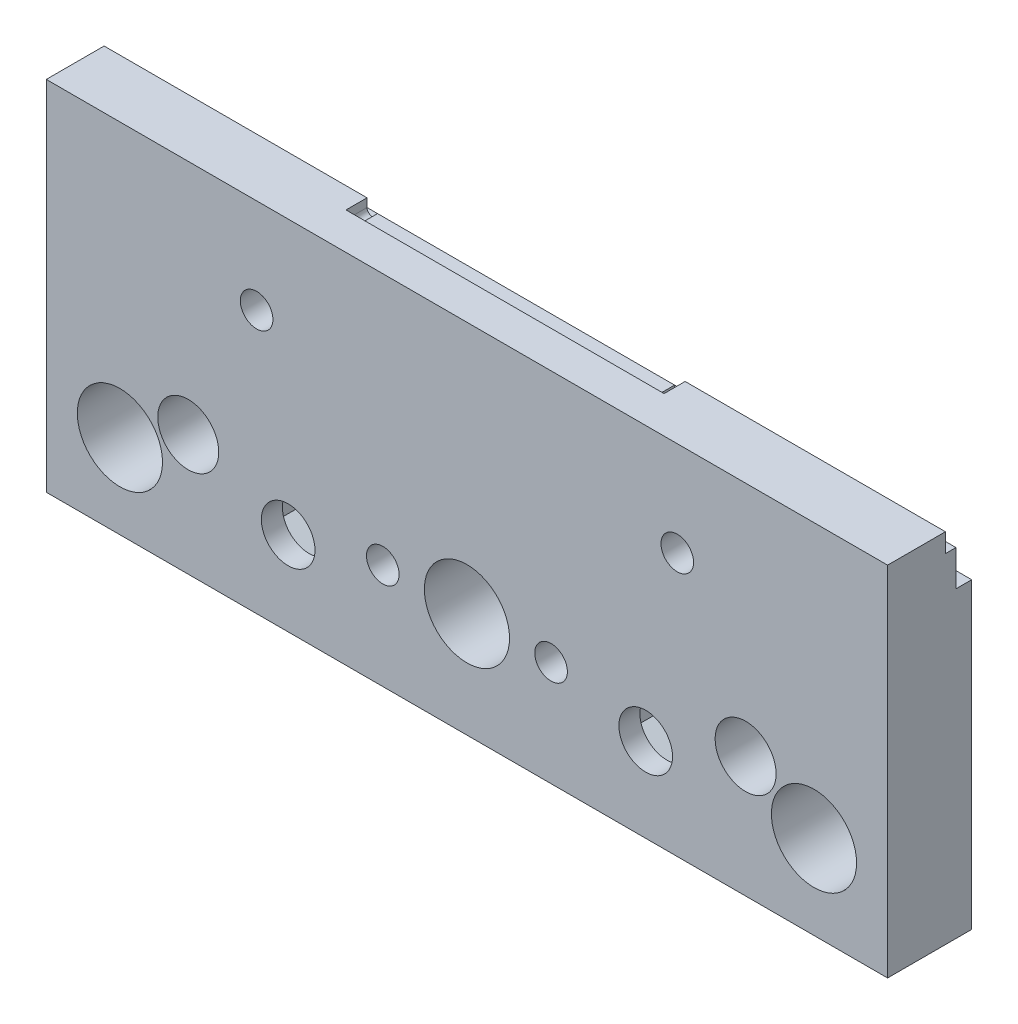
SolidWorks part; units mm, degrees
ref_plane "前视基准面" through (0, 0, 0) normal (0, 0, 1) x (1, 0, 0)
ref_plane "上视基准面" through (0, 0, 0) normal (0, 1, 0) x (1, 0, 0)
ref_plane "右视基准面" through (0, 0, 0) normal (1, 0, 0) x (0, 0, -1)
sketch "前视图草图" plane through (0, 0, 0) normal (0, 0, 1) x (1, 0, 0)
  line L0 (0, 0) -> (44.4821, 0) construction
  line L1 (0, 0) -> (0, 28.3185) construction
sketch "草图2" plane through (0, 0, 0) normal (0, 0, 1) x (1, 0, 0)
  line L0 (0, 0) -> (80, 0)
  line L1 (-200000, 0) -> (200044.4821, 0) construction
  line L2 (80, 0) -> (80, 34)
  line L3 (80, 34) -> (0, 34)
  line L4 (0, -200000) -> (0, 200028.3185) construction
  line L5 (0, 34) -> (0, 0)
  circle A0 centre (7, 8) radius 4.05
  circle A1 centre (40, 10) radius 4.05
  circle A2 centre (73, 8) radius 4.05
  dimension "D3" = 8
  dimension "D5" = 10
  dimension "D9" = 8.1
  dimension "D10" = 8.1
  dimension "D11" = 8.1
  dimension "D1" = 34
  dimension "D2" = 80
  dimension "D4" = 7
  dimension "D6" = 7
  dimension "D7" = 8
  dimension "D8" = 40
extrude "凸台-拉伸1" add sketch "草图2" along normal blind 8
sketch "草图3" plane through (0, 0, 8) normal (0, 0, 1) x (1, 0, 0)
  line L0 (16.088, 8) -> (31.4805, 8) construction
  line L1 (7, 8) -> (7, 16.8386) construction
  line L2 (73, 8) -> (73, 16.5917) construction
  line L4 (-200000, 0) -> (200044.4821, 0) construction
  circle A2 centre (23, 8) radius 2.55
  circle A3 centre (57, 8) radius 2.55
  dimension "D4" = 5.1
  dimension "D5" = 5.1
  dimension "D1" = 8
  dimension "D2" = 16
  dimension "D3" = 16
extrude "切除-拉伸1" cut sketch "草图3" against normal through all
sketch "草图4" plane through (80, 0, 0) normal (1, 0, 0) x (0, 0, -1)
  line L1 (0, -200000) -> (0, 200028.3185) construction
  line L2 (-1.5, 32.2) -> (-2.5, 32.2)
  line L3 (-2.5, 32.2) -> (-2.5, 34)
  line L4 (-8, 34) -> (0, 34) construction
  line L5 (-2.5, 34) -> (0, 34)
  line L6 (-1.5, 32.2) -> (-1.5, 28.8)
  line L7 (-1.5, 28.8) -> (0, 28.8)
  line L8 (0, 28.8) -> (0, 34)
  dimension "D1" = 3.4
  dimension "D2" = 2.5
  dimension "D3" = 1.5
  dimension "D4" = 1.8
extrude "切除-拉伸2" cut sketch "草图4" against normal through all
sketch "草图5" plane through (0, 0, 8) normal (0, 0, 1) x (1, 0, 0)
  line L0 (40, 10) -> (56.5376, 10) construction
  circle A0 centre (40, 10) radius 8 construction
  circle A1 centre (48, 10) radius 1.55
  circle A2 centre (32, 10) radius 1.55
  dimension "D1" = 3.1
  dimension "D2" = 3.1
  dimension "D3" = 16
extrude "切除-拉伸3" cut sketch "草图5" against normal through all
sketch "草图7" plane through (0, 0, 0) normal (0, 0, -1) x (-1, 0, 0)
  line L0 (-40, 12) -> (-40, -8.3696) construction
  line L1 (-23, 10) -> (-23, -2.3368) construction
  line L2 (200000, 0) -> (-200044.4821, 0) construction
  line L6 (-27.05, 10) -> (-27.05, 2.5)
  line L7 (-29.55, 0) -> (-16.45, 0)
  line L8 (-18.95, 2.5) -> (-18.95, 10)
  line L9 (-23, 8) -> (-23, 15.9045) construction
  line L13 (0, -200000) -> (0, 200028.3185) construction
  line L14 (-57, 8) -> (-57, 15.9045) construction
  line L15 (-57, 10) -> (-57, -2.3368) construction
  line L16 (-61.05, 2.5) -> (-61.05, 10)
  line L17 (-50.45, 0) -> (-63.55, 0)
  line L18 (-52.95, 10) -> (-52.95, 2.5)
  arc A1 (-18.95, 10) -> (-27.05, 10) centre (-23, 10) ccw
  arc A4 (-29.55, 0) -> (-27.05, 2.5) centre (-29.55, 2.5) ccw
  arc A5 (-18.95, 2.5) -> (-16.45, 0) centre (-16.45, 2.5) ccw
  arc A7 (-61.05, 2.5) -> (-63.55, 0) centre (-63.55, 2.5) cw
  arc A8 (-50.45, 0) -> (-52.95, 2.5) centre (-50.45, 2.5) cw
  arc A9 (-61.05, 10) -> (-52.95, 10) centre (-57, 10) cw
  dimension "D1" = 40
  dimension "D4" = 8.1
  dimension "D7" = 2.5
  dimension "D8" = 2.5
  dimension "D3" = 10
extrude "切除-拉伸4" [suppressed] cut sketch "草图7" against normal blind 6
sketch "草图8" plane through (0, 0, 0) normal (0, 0, -1) x (-1, 0, 0)
  line L0 (-40, 10) -> (-57.3165, 10) construction
  line L1 (-40, 20) -> (-40, 35.6562) construction
  line L2 (-30.5, 12.85) -> (-49.5, 12.85)
  line L3 (-49.5, 7.15) -> (-30.5, 7.15)
  line L4 (200000, 0) -> (-200044.4821, 0) construction
  line L5 (-80, 0) -> (-80, 28.8) construction
  line L6 (-48, 6.7091) -> (-45.15, 8.3546)
  line L7 (-45.15, 8.3546) -> (-45.15, 11.6454)
  line L8 (-45.15, 11.6454) -> (-48, 13.2909)
  line L9 (-48, 13.2909) -> (-50.85, 11.6454)
  line L10 (-50.85, 11.6454) -> (-50.85, 8.3546)
  line L11 (-50.85, 8.3546) -> (-48, 6.7091)
  line L12 (-34.85, 11.6454) -> (-34.85, 8.3546)
  line L13 (-34.85, 8.3546) -> (-32, 6.7091)
  line L14 (-32, 6.7091) -> (-29.15, 8.3546)
  line L15 (-29.15, 8.3546) -> (-29.15, 11.6454)
  line L16 (-29.15, 11.6454) -> (-32, 13.2909)
  line L17 (-32, 13.2909) -> (-34.85, 11.6454)
  arc A0 (-30.5, 7.15) -> (-30.5, 12.85) centre (-30.5, 10) ccw
  arc A1 (-49.5, 12.85) -> (-49.5, 7.15) centre (-49.5, 10) ccw
  circle A2 centre (-48, 10) radius 2.85 construction
  circle A3 centre (-32, 10) radius 2.85 construction
  dimension "D1" = 5.7
  dimension "D2" = 9.5
  dimension "D3" = 9.5
  dimension "D4" = 10
  dimension "D5" = 5.7
sketch "草图11" plane through (0, 0, 0) normal (0, 0, -1) x (-1, 0, 0)
  line L0 (0, 34) -> (-80, 34) construction
  line L1 (-80, 0) -> (-80, 28.8) construction
  line L2 (0, -200000) -> (0, 200028.3185) construction
  line L3 (-40, 20) -> (-40, 13.5744) construction
  line L4 (-28.772, 25) -> (-45.9396, 25) construction
  circle A0 centre (-60, 25) radius 1.55
  circle A1 centre (-20, 25) radius 1.55
  point P23 (-40, 20)
  dimension "D1" = 3.1
  dimension "D2" = 3.1
  dimension "D3" = 20
  dimension "D4" = 20
  dimension "D5" = 9
sketch "草图20" plane through (0, 0, 0) normal (0, 0, -1) x (-1, 0, 0)
  circle A0 centre (-40, 10) radius 5.5
  dimension "D1" = 11
extrude "切除-拉伸15" cut sketch "草图8" against normal blind 4.5 contours L10 L11 L6 L7 L8 L9 | L13 L14 L15 L16 L17 L12
extrude "切除-拉伸7" cut sketch "草图11" against normal through all contours A0 | A1
sketch "草图12" plane through (0, 0, 0) normal (0, 0, -1) x (-1, 0, 0)
  line L0 (-62.5, 22.15) -> (-57.5, 22.15)
  line L1 (-57.5, 27.85) -> (-62.5, 27.85)
  line L4 (-80, 0) -> (-80, 28.8) construction
  line L5 (-39.1423, 25) -> (-43.2672, 25) construction
  line L6 (-60, 21) -> (-60, 25.2385) construction
  line L7 (-20, 21) -> (-20, 26.1603) construction
  line L8 (-40, 20) -> (-40, 24.3689) construction
  line L9 (-17.5, 27.85) -> (-22.5, 27.85)
  line L10 (-22.5, 22.15) -> (-17.5, 22.15)
  line L11 (0, -200000) -> (0, 200028.3185) construction
  line L12 (0, 34) -> (-80, 34) construction
  arc A0 (-62.5, 27.85) -> (-62.5, 22.15) centre (-62.5, 25) ccw
  arc A1 (-57.5, 22.15) -> (-57.5, 27.85) centre (-57.5, 25) ccw
  arc A4 (-17.5, 22.15) -> (-17.5, 27.85) centre (-17.5, 25) ccw
  arc A5 (-22.5, 27.85) -> (-22.5, 22.15) centre (-22.5, 25) ccw
  point P16 (-38, 21)
  point P28 (-40, 25)
  dimension "D2" = 20
  dimension "D3" = 5
  dimension "D4" = 2.5
  dimension "D5" = 20
  dimension "D6" = 9
  dimension "D1" = 2
sketch "草图19" plane through (0, 0, 2.5) normal (0, 0, -1) x (-1, 0, 0)
  line L0 (0, 34) -> (-80, 34) construction
  line L1 (-25, 34) -> (-55.2479, 34)
  line L2 (-25, 34) -> (-25, 33.2)
  line L3 (-26, 33.2) -> (-54.2479, 33.2)
  line L4 (-55.2479, 34) -> (-55.2479, 33.2)
  line L5 (0, -200000) -> (0, 200028.3185) construction
  line L7 (0, 32.2) -> (-80, 32.2) construction
  line L8 (-56.3335, 32.7) -> (-52.9089, 32.7) construction
  line L9 (-55.2479, 1028.5823) -> (-55.2479, 33.2) construction
  line L10 (-25, 1028.5823) -> (-25, 32.7) construction
  line L11 (-55.2479, 32.7) -> (-55.2479, -973.3) construction
  line L12 (-25, 32.7) -> (-25, -973.3) construction
  arc A3 (-55.2479, 33.2) -> (-54.2479, 33.2) centre (-54.7479, 33.2) ccw
  arc A6 (-26, 33.2) -> (-25, 33.2) centre (-25.5, 33.2) ccw
  dimension "D3" = 1
  dimension "D4" = 1
  dimension "D2" = 0.8
  dimension "D1" = 0.5
  dimension "D9" = 25
extrude "切除-拉伸11" cut sketch "草图19" against normal blind 2
sketch "草图21" plane through (0, 0, 0) normal (0, 0, -1) x (-1, 0, 0)
  line L0 (-80, 11.5) -> (0, 11.5) construction
  line L1 (-80, 0) -> (-80, 28.8) construction
  line L2 (0, -200000) -> (0, 200028.3185) construction
  line L3 (-66.5, 28.8) -> (-66.5, 0) construction
  line L4 (0, 28.8) -> (-80, 28.8) construction
  line L5 (200000, 0) -> (-200044.4821, 0) construction
  line L6 (-40, 28.8) -> (-40, 0) construction
  line L7 (-40, -199980) -> (-40, 200024.3689) construction
  circle A0 centre (-66.5, 11.5) radius 2.9
  circle A1 centre (-13.5, 11.5) radius 2.9
  dimension "D3" = 5.8
  dimension "D1" = 11.5
  dimension "D2" = 13.5
extrude "切除-拉伸13" cut sketch "草图21" against normal through all
sketch "草图22" plane through (0, 0, 0) normal (0, 0, -1) x (-1, 0, 0)
  line L0 (-80, 0) -> (-80, 28.8) construction
  line L1 (-52.9, 5.6329) -> (-52.9, 10.3671)
  line L2 (-52.9, 10.3671) -> (-57, 12.7343)
  line L3 (-57, 12.7343) -> (-61.1, 10.3671)
  line L4 (-61.1, 10.3671) -> (-61.1, 5.6329)
  line L5 (-61.1, 5.6329) -> (-57, 3.2657)
  line L6 (-57, 3.2657) -> (-52.9, 5.6329)
  line L7 (-23, 3.2657) -> (-18.9, 5.6329)
  line L8 (-18.9, 5.6329) -> (-18.9, 10.3671)
  line L9 (-18.9, 10.3671) -> (-23, 12.7343)
  line L10 (-23, 12.7343) -> (-27.1, 10.3671)
  line L11 (-27.1, 10.3671) -> (-27.1, 5.6329)
  line L12 (-27.1, 5.6329) -> (-23, 3.2657)
  circle A0 centre (-57, 8) radius 4.1 construction
  circle A1 centre (-23, 8) radius 4.1 construction
  dimension "D1" = 8.2
extrude "切除-拉伸14" cut sketch "草图22" against normal blind 6
